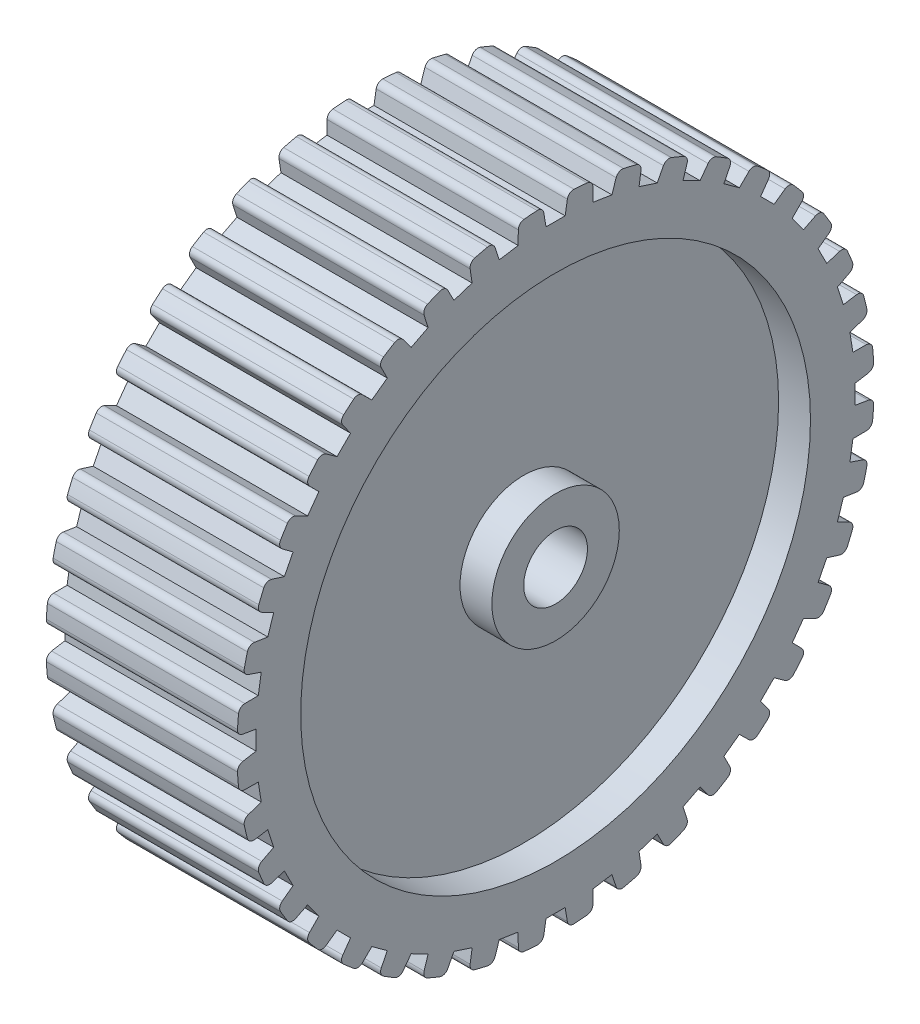
SolidWorks part; units mm, degrees
ref_plane "Front Plane" through (0, 0, 0) normal (0, 0, 1) x (1, 0, 0)
ref_plane "Top Plane" through (0, 0, 0) normal (0, 1, 0) x (1, 0, 0)
ref_plane "Right Plane" through (0, 0, 0) normal (1, 0, 0) x (0, 0, -1)
sketch "Sketch1" plane through (0, 0, 0) normal (0, 0, 1) x (1, 0, 0)
  line L0 (0, 0) -> (-52.2034, 0) construction
  line L1 (0, 5) -> (-30, 5)
  line L2 (-30, 5) -> (-30, 10)
  line L3 (-30, 10) -> (-25, 10)
  line L4 (-25, 10) -> (-25, 40)
  line L5 (-25, 40) -> (-30, 40)
  line L6 (-30, 40) -> (-30, 50)
  line L7 (-30, 50) -> (0, 50)
  line L8 (0, 50) -> (0, 40)
  line L9 (0, 40) -> (-5, 40)
  line L10 (-5, 40) -> (-5, 10)
  line L11 (-5, 10) -> (0, 10)
  line L12 (0, 10) -> (0, 5)
  dimension "D1" = 10
  dimension "D2" = 100
  dimension "D3" = 30
  dimension "D4" = 20
  dimension "D5" = 5
  dimension "D6" = 10
revolve "Revolve1" add sketch "Sketch1" angle 360 about L0
sketch "Sketch2" plane through (0, 0, 0) normal (1, 0, 0) x (0, 0, -1)
  line L0 (-2.5, 53) -> (-1.5, 47)
  line L1 (-1.5, 47) -> (1.5, 47)
  line L2 (1.5, 47) -> (2.5, 53)
  line L3 (2.5, 53) -> (-2.5, 53)
  circle A0 centre (0, 0) radius 50 construction
  point P3 (0, 47)
  point P6 (0, 53)
  point P7 (0, 50)
  dimension "D1" = 3
  dimension "D2" = 5
  dimension "D3" = 6
  dimension "D4" = 3
extrude "Cut-Extrude1" cut sketch "Sketch2" against normal blind 44
fillet "Fillet1" radius 1 2 edges at (-15, 49.9602, 1.9934) (-15, 49.9602, -1.9934)
pattern_circular "CirPattern1" count 40 over 360 about axis through (0, 0, 0) along (1, 0, 0) of "Cut-Extrude1", "Fillet1"
